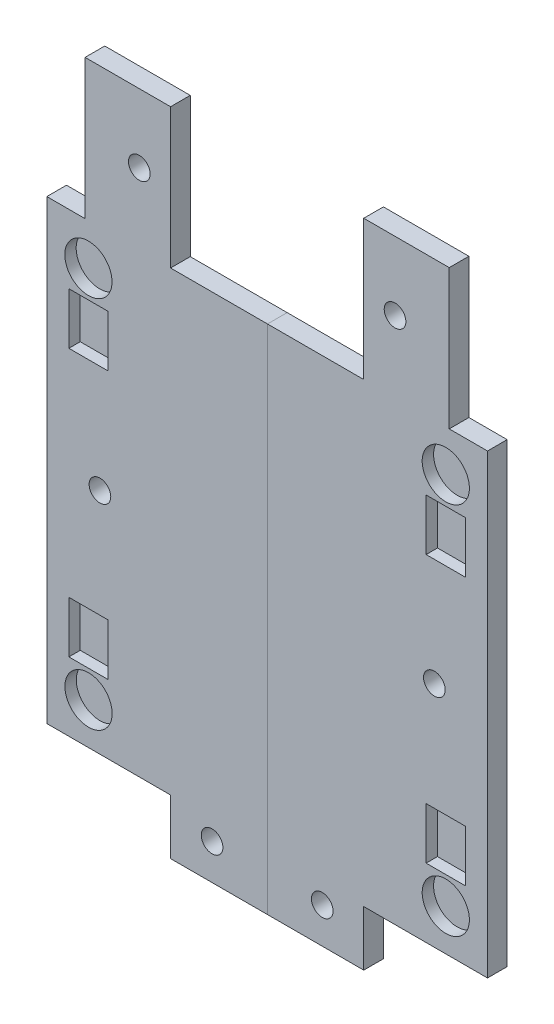
SolidWorks part; units mm, degrees
ref_plane "Front Plane" through (0, 0, 0) normal (0, 0, 1) x (1, 0, 0)
ref_plane "Top Plane" through (0, 0, 0) normal (0, 1, 0) x (1, 0, 0)
ref_plane "Right Plane" through (0, 0, 0) normal (1, 0, 0) x (0, 0, -1)
sketch "Sketch1" plane through (0, 0, 0) normal (0, 0, 1) x (1, 0, 0)
  line L0 (-24.5467, 142.7703) -> (0.082, 142.7703)
  line L1 (-55.9999, 142.7703) -> (-46.2733, 142.7703)
  line L2 (-55.9999, 142.7703) -> (-55.9999, 26.7703)
  line L3 (-55.9999, 26.7703) -> (-24.5467, 26.7703)
  line L4 (0.082, 142.7703) -> (0.082, 26.7703)
  line L5 (0.082, 12.7703) -> (-24.5467, 12.7703)
  line L6 (0.082, 12.7703) -> (0.082, 26.7703)
  line L8 (-24.5467, 12.7703) -> (-24.5467, 26.7703)
  line L9 (-46.2733, 178.2703) -> (-24.5467, 178.2703)
  line L10 (-46.2733, 178.2703) -> (-46.2733, 142.7703)
  line L12 (-24.5467, 178.2703) -> (-24.5467, 142.7703)
  dimension "D1" = 21.7266
  dimension "D2" = 35.5
  dimension "D3" = 116
  dimension "D4" = 14
  dimension "D5" = 24.6287
  dimension "D6" = 116
  dimension "D7" = 24.6287
extrude "Boss-Extrude1" add sketch "Sketch1" against normal blind 5
sketch "Sketch3" plane through (0, 0, 0) normal (0, 0, 1) x (1, 0, 0)
  line L0 (24.5467, 12.7703) -> (-24.5467, 12.7703) construction
  line L1 (-24.5467, 26.7703) -> (-24.5467, 12.7703) construction
  line L2 (-55.9999, 142.7703) -> (-55.9999, 26.7703) construction
  line L3 (-55.9999, 26.7703) -> (-24.5467, 26.7703) construction
  line L4 (-24.5467, 142.7703) -> (-24.5467, 178.2703) construction
  line L5 (-24.5467, 178.2703) -> (-46.2733, 178.2703) construction
  circle A0 centre (-14, 21.8524) radius 2.75
  circle A1 centre (-42.5001, 84.806) radius 2.75
  circle A2 centre (-32.5, 160.8524) radius 2.75
  dimension "D1" = 9.0821
  dimension "D2" = 10.5467
  dimension "D3" = 13.4999
  dimension "D4" = 58.0357
  dimension "D5" = 7.9532
  dimension "D6" = 17.4179
extrude "Cut-Extrude1" cut sketch "Sketch3" against normal through all
sketch "Sketch4" plane through (0, 0, 0) normal (0, 0, 1) x (1, 0, 0)
  line L1 (-50.4, 44.2487) -> (-40.4, 44.2487)
  line L2 (-50.4, 44.2487) -> (-50.4, 57.3688)
  line L3 (-50.4, 57.3688) -> (-40.4, 57.3688)
  line L4 (-40.4, 44.2487) -> (-40.4, 57.3688)
  line L5 (-50.4, 112.1717) -> (-40.4, 112.1717)
  line L6 (-50.4, 112.1717) -> (-50.4, 125.2919)
  line L7 (-50.4, 125.2919) -> (-40.4, 125.2919)
  line L8 (-40.4, 112.1717) -> (-40.4, 125.2919)
  circle A0 centre (-45.4, 37.2703) radius 6
  circle A1 centre (-45.4291, 132.2703) radius 6.0001
extrude "Cut-Extrude4" cut sketch "Sketch4" against normal blind 2.89
sketch "Sketch5" plane through (0, 0, 0) normal (0, 0, 1) x (1, 0, 0)
  line L0 (46.2733, 142.7703) -> (55.9999, 142.7703)
  line L1 (24.5467, 178.2703) -> (46.2733, 178.2703)
  line L2 (24.5467, 178.2703) -> (24.5467, 142.7703)
  line L4 (46.2733, 178.2703) -> (46.2733, 142.7703)
  line L5 (0.082, 142.7703) -> (24.5467, 142.7703)
  line L6 (0.082, 142.7703) -> (0.082, 26.7703)
  line L7 (24.5467, 26.7703) -> (55.9999, 26.7703)
  line L8 (55.9999, 142.7703) -> (55.9999, 26.7703)
  line L9 (24.5467, 12.7703) -> (0.082, 12.7703)
  line L10 (24.5467, 12.7703) -> (24.5467, 26.7703)
  line L12 (0.082, 12.7703) -> (0.082, 26.7703)
  dimension "D1" = 116
  dimension "D2" = 35.5
  dimension "D3" = 14
  dimension "D4" = 55.9179
  dimension "D5" = 24.4647
  dimension "D6" = 21.7266
extrude "Boss-Extrude2" add sketch "Sketch5" against normal blind 5 separate body
sketch "Sketch6" plane through (0, 0, 0) normal (0, 0, 1) x (1, 0, 0)
  line L0 (0.082, 12.7703) -> (24.5467, 12.7703) construction
  line L2 (24.5467, 12.7703) -> (24.5467, 26.7703) construction
  line L3 (55.9999, 26.7703) -> (55.9999, 142.7703) construction
  line L4 (55.9999, 142.7703) -> (46.2733, 142.7703) construction
  line L5 (24.5467, 178.2703) -> (24.5467, 142.7703) construction
  line L6 (46.2733, 178.2703) -> (24.5467, 178.2703) construction
  circle A0 centre (32.5, 160.8524) radius 2.75
  circle A1 centre (42.5001, 84.806) radius 2.75
  circle A2 centre (14, 21.8524) radius 2.75
  dimension "D1" = 9.0821
  dimension "D2" = 10.5468
  dimension "D3" = 13.4999
  dimension "D4" = 57.9643
  dimension "D5" = 7.9532
  dimension "D6" = 17.4179
extrude "Cut-Extrude5" cut sketch "Sketch6" against normal through all
sketch "Sketch7" plane through (0, 0, 0) normal (0, 0, 1) x (1, 0, 0)
  line L1 (40.4, 125.2919) -> (50.4, 125.2919)
  line L2 (40.4, 125.2919) -> (40.4, 112.1717)
  line L3 (40.4, 112.1717) -> (50.4, 112.1717)
  line L4 (50.4, 125.2919) -> (50.4, 112.1717)
  line L5 (40.4, 57.3688) -> (50.4, 57.3688)
  line L6 (40.4, 57.3688) -> (40.4, 44.2487)
  line L7 (40.4, 44.2487) -> (50.4, 44.2487)
  line L8 (50.4, 57.3688) -> (50.4, 44.2487)
  circle A0 centre (45.4, 132.2703) radius 6
  circle A1 centre (45.4, 37.2703) radius 6
extrude "Cut-Extrude13" cut sketch "Sketch7" against normal blind 2.89
